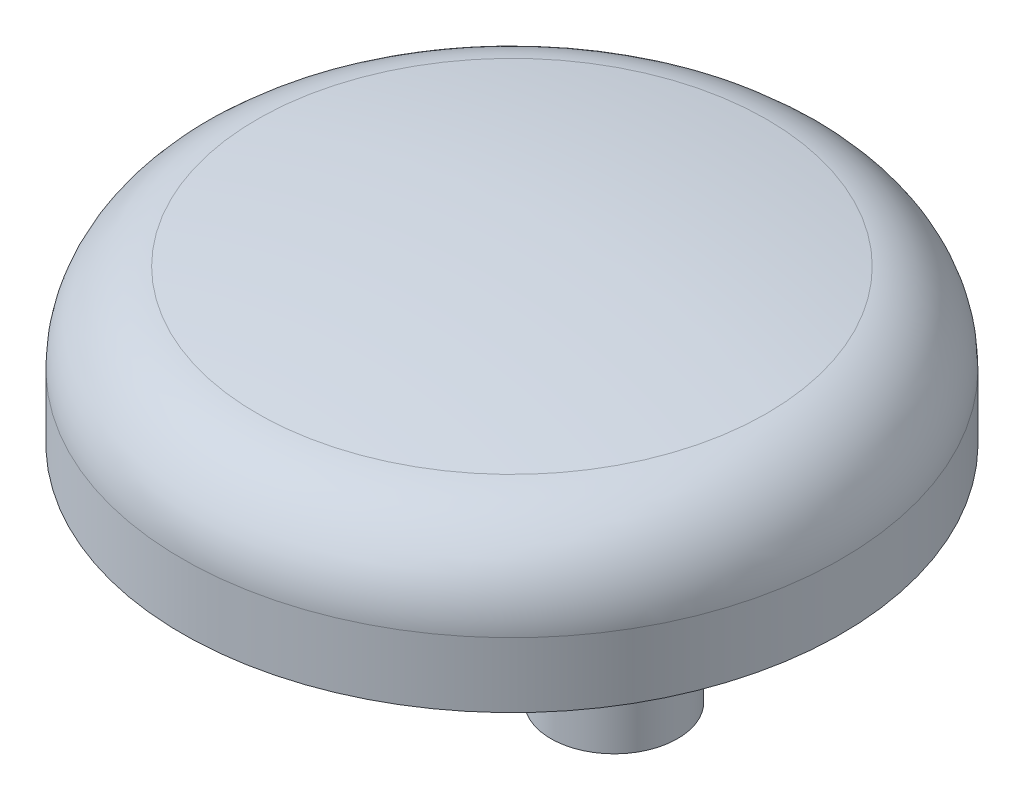
SolidWorks part; units mm, degrees
ref_plane "Front Plane" through (0, 0, 0) normal (0, 0, 1) x (1, 0, 0)
ref_plane "Top Plane" through (0, 0, 0) normal (0, 1, 0) x (1, 0, 0)
ref_plane "Right Plane" through (0, 0, 0) normal (1, 0, 0) x (0, 0, -1)
sketch "Sketch3" plane through (0, 0, 0) normal (0, 0, 1) x (1, 0, 0)
  line L0 (0, 0) -> (33.02, 0)
  line L1 (0, 0) -> (0, 17.526)
  line L2 (0, -21.5758) -> (0, 0) construction
  line L3 (33.02, 0) -> (33.02, 6.5)
  arc A0 (25.5275, 15.3728) -> (0, 17.526) centre (0, -134.874) ccw
  arc A1 (33.02, 6.5) -> (25.5275, 15.3728) centre (24.02, 6.5) ccw
  dimension "D3" = 9
  dimension "D4" = 152.4
  dimension "D1" = 33.02
  dimension "D2" = 17.526
revolve "Revolve1" add sketch "Sketch3" angle 360 about L2
sketch "Sketch4" plane through (0, 0, 0) normal (0, -1, 0) x (1, 0, 0)
  line L0 (0, 0) -> (33.02, 0) construction
  line L1 (0, 0) -> (0, 33.02) construction
  circle A1 centre (6.477, -3.77) radius 6.35
  dimension "D3" = 12.7
  dimension "D1" = 6.477
  dimension "D2" = 3.77
extrude "Boss-Extrude2" add sketch "Sketch4" along normal blind 21.082
